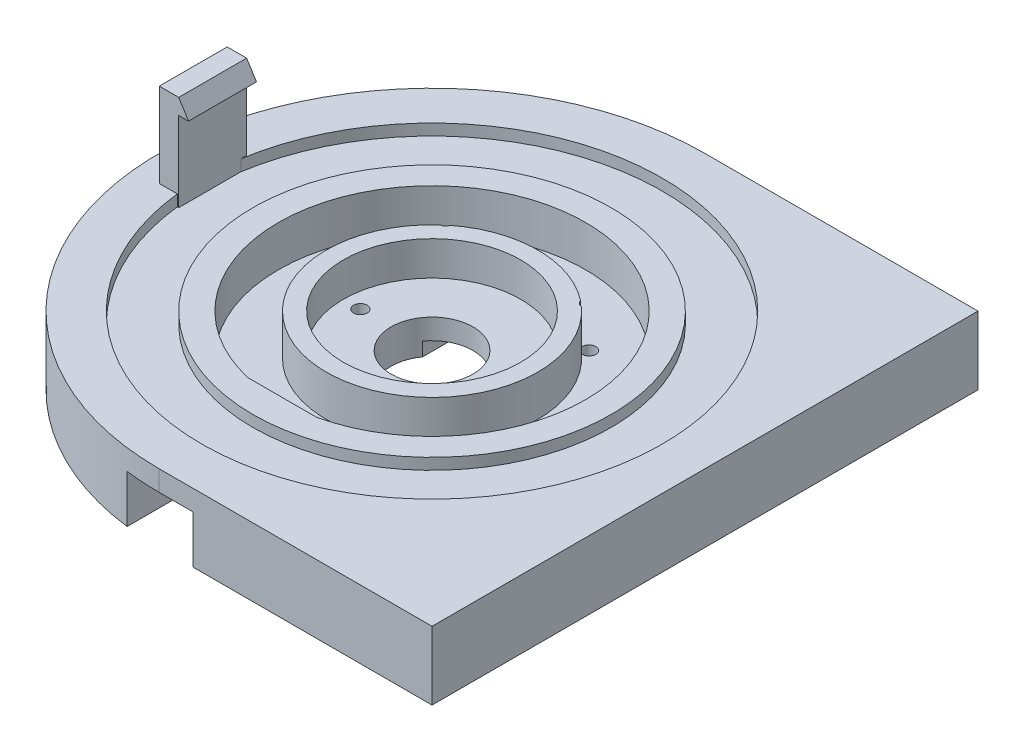
SolidWorks part; units mm, degrees
ref_plane "Front Plane" through (0, 0, 0) normal (0, 0, 1) x (1, 0, 0)
ref_plane "Top Plane" through (0, 0, 0) normal (0, 1, 0) x (1, 0, 0)
ref_plane "Right Plane" through (0, 0, 0) normal (1, 0, 0) x (0, 0, -1)
sketch "Sketch28" plane through (0, 0, 0) normal (0, 1, 0) x (1, 0, 0)
  line L1 (-38.0554, -35.7587) -> (41.9446, -35.7587)
  line L2 (-38.0554, -35.7587) -> (-38.0554, 44.2413)
  line L3 (-38.0554, 44.2413) -> (41.9446, 44.2413)
  line L4 (41.9446, -35.7587) -> (41.9446, 44.2413)
  dimension "D1" = 80
extrude "Boss-Extrude1" add sketch "Sketch28" along normal blind 10
hole_wizard "CBORE for M10 Cheese Head Screw1" positions "Sketch30" profile "Sketch29" counterbore size "M10" standard "AS" end condition through all
sketch "Sketch30" plane through (0, 10, 0) normal (0, 1, 0) x (1, 0, 0)
  point P0 (1.9446, 4.2413)
sketch "Sketch29" plane through (1.9446, 10, -4.2413) normal (1, 0, 0) x (0, 0, 1)
  line L0 (0, 0) -> (0, 10)
  line L1 (0, 10) -> (6, 10)
  line L3 (6, 10) -> (6, 5)
  line L4 (6, 5) -> (13, 5)
  line L5 (13, 5) -> (13, 0)
  line L7 (13, 0) -> (0, 0)
  line L11 (0, -6.35) -> (0, 107.95) construction
  dimension "Thru Hole Dia." = 12
  dimension "Thru Hole Depth" = 10
  dimension "C'Bore Dia." = 26
  dimension "C'Bore Depth" = 5
sketch "Sketch36" plane through (0, 0, 0) normal (0, -1, 0) x (1, 0, 0)
  circle A0 centre (12.4446, -16.7413) radius 1
  circle A1 centre (12.4446, -4.2413) radius 1
  circle A2 centre (-8.5554, -16.7413) radius 1
  circle A3 centre (-8.5554, -4.2413) radius 1
sketch "Sketch37" plane through (0, 10, 0) normal (0, 1, 0) x (1, 0, 0)
  line L0 (1.9446, 44.2413) -> (1.9446, -35.7587) construction
  line L1 (41.9446, 44.2413) -> (-38.0554, 44.2413) construction
  line L2 (-38.0554, -35.7587) -> (41.9446, -35.7587) construction
  line L3 (-38.0554, 4.2413) -> (41.9446, 4.2413) construction
  line L4 (-38.0554, 44.2413) -> (-38.0554, -35.7587) construction
  line L5 (41.9446, -35.7587) -> (41.9446, 44.2413) construction
  circle A0 centre (1.9446, 4.2413) radius 22.5
  circle A1 centre (1.9446, 4.2413) radius 15.5
  dimension "D1" = 31
  dimension "D2" = 45
extrude "Cut-Extrude2" cut sketch "Sketch37" against normal blind 6
sketch "Sketch39" plane through (0, 10, 0) normal (0, 1, 0) x (1, 0, 0)
  line L0 (41.9446, 44.2413) -> (-38.0554, 44.2413) construction
  line L1 (10.8724, 24.8942) -> (-5.6612, 24.8942)
  line L2 (10.8724, 24.8942) -> (10.8724, 44.2413)
  line L3 (10.8724, 44.2413) -> (-5.6612, 44.2413)
  line L4 (-5.6612, 24.8942) -> (-5.6612, 44.2413)
  line L5 (1.9446, -35.7587) -> (6.9446, -35.7587)
  line L6 (-38.0554, -35.7587) -> (41.9446, -35.7587) construction
  line L7 (6.9446, -35.7587) -> (-3.0554, -35.7587)
  line L8 (-3.0554, -35.7587) -> (-3.0554, -17.6961)
  line L9 (-3.0554, -17.6961) -> (6.9446, -17.6961)
  line L10 (6.9446, -17.6961) -> (6.9446, -35.7587)
  circle A0 centre (1.9446, 4.2413) radius 22.5 construction
  circle M5 centre (1.9446, 4.2413) radius 22.5
  line M7 (-38.0554, -35.7587) -> (41.9446, -35.7587)
extrude "Cut-Extrude6" cut sketch "Sketch39" against normal blind 6 contours L10 L8 M5 M7
sketch "Sketch40" plane through (-3.0554, 0, 0) normal (1, 0, 0) x (0, 0, -1)
  line L0 (-35.7587, 4) -> (-35.7587, 10) construction
  line L1 (-35.7587, 7) -> (-17.6961, 7)
  line L2 (-35.7587, 7) -> (-35.7587, 10)
  line L3 (-35.7587, 10) -> (-17.6961, 10)
  line L4 (-17.6961, 7) -> (-17.6961, 10)
extrude "Boss-Extrude7" add sketch "Sketch40" along normal blind 13
sketch "Sketch41" plane through (0, 10, 0) normal (0, 1, 0) x (1, 0, 0)
  circle A0 centre (1.9446, 4.2413) radius 33.75
  circle A1 centre (1.9446, 4.2413) radius 26.25
  dimension "D1" = 67.5
sketch "Sketch47" plane through (0, 4, 0) normal (0, 1, 0) x (1, 0, 0)
  line L0 (-3.0554, -35.7587) -> (-3.0554, -17.6961) construction
  line L1 (-3.0554, -26.7274) -> (6.9446, -26.7274)
  line L2 (-3.0554, -26.7274) -> (-3.0554, -35.7587)
  line L3 (-3.0554, -35.7587) -> (6.9446, -35.7587)
  line L4 (6.9446, -26.7274) -> (6.9446, -35.7587)
extrude "Cut-Extrude12" cut sketch "Sketch47" against normal blind 10
extrude "Cut-Extrude7" cut sketch "Sketch41" against normal blind 1.65
sketch "Sketch42" plane through (0, 0, 0) normal (0, -1, 0) x (1, 0, 0)
  line L2 (6.8666, -7.591) -> (6.8666, -18.6283)
  line L3 (-2.9334, -18.6283) -> (-2.9334, -7.591)
  line L4 (6.8666, -7.591) -> (-2.9334, -7.591)
  line L5 (6.8666, -18.6283) -> (-2.9334, -18.6283)
extrude "Cut-Extrude13" cut sketch "Sketch36" against normal blind 10
extrude "Cut-Extrude8" cut sketch "Sketch42" against normal blind 2
sketch "Sketch43" plane through (0, 10, 0) normal (0, 1, 0) x (1, 0, 0)
  line L1 (41.9446, 44.2413) -> (-38.0554, 44.2413) construction
  line L2 (1.9446, 44.2413) -> (41.9446, 44.2413)
  line L3 (41.9446, 44.2413) -> (41.9446, -35.7587)
  line L5 (1.9446, 44.2413) -> (-38.0554, 44.2413)
  line L6 (-38.0554, 44.2413) -> (-38.0554, -35.7587)
  line L7 (41.9446, 4.2413) -> (-38.0554, 4.2413) construction
  line L8 (1.9446, -35.7587) -> (41.9446, -35.7587)
  line L9 (1.9446, -35.7587) -> (-38.0554, -35.7587)
  arc A1 (1.9446, -35.7587) -> (1.9446, 44.2413) centre (1.9446, 4.2413) ccw
  arc A2 (1.9446, 44.2413) -> (1.9446, -35.7587) centre (1.9446, 4.2413) ccw
  line M5 (-38.0554, -35.7587) -> (41.9446, -35.7587)
  line M7 (41.9446, 44.2413) -> (-38.0554, 44.2413)
  line M8 (-38.0554, 44.2413) -> (-38.0554, -35.7587)
extrude "Cut-Extrude11" cut sketch "Sketch43" against normal blind 20 contours A2 M7 M8 | A2 L6 M5
sketch "Sketch45" plane through (0, 8.35, 0) normal (0, 1, 0) x (1, 0, 0)
  line L1 (-34.2365, 10.408) -> (-31.3854, 10.408)
  line L2 (-34.2365, 10.408) -> (-34.2365, 0.4527)
  line L3 (-34.2365, 0.4527) -> (-31.3854, 0.4527)
  line L4 (-31.3854, 10.408) -> (-31.3854, 0.4527)
extrude "Boss-Extrude8" add sketch "Sketch45" along normal blind 14
sketch "Sketch46" plane through (0, 0, -0.4527) normal (0, 0, 1) x (1, 0, 0)
  line L0 (-31.3854, 22.35) -> (-31.3854, 20.0572)
  line L1 (-31.3854, 22.35) -> (-31.3854, 8.35) construction
  line L2 (-31.3854, 20.0572) -> (-29.9445, 20.0572)
  line L3 (-29.9445, 20.0572) -> (-31.3854, 22.35)
extrude "Boss-Extrude9" add sketch "Sketch46" against normal up to vertex
